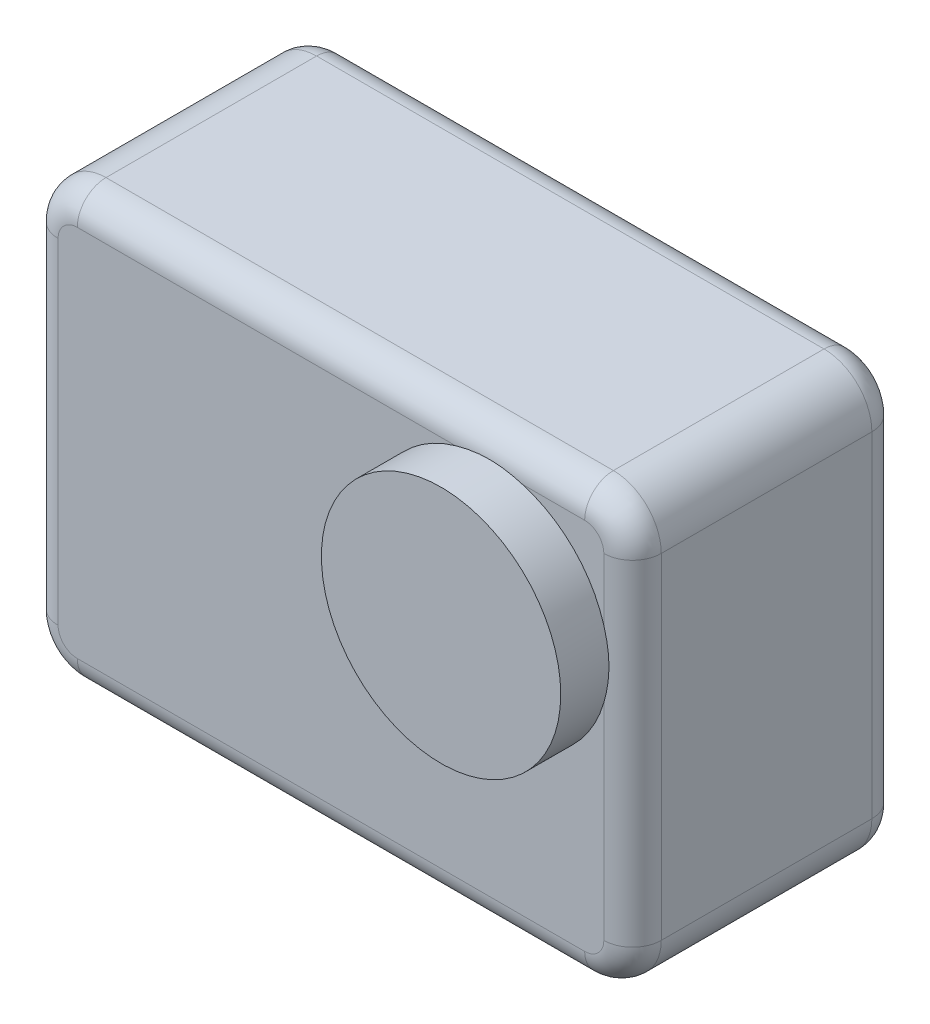
SolidWorks part; units mm, degrees
ref_plane "Front Plane" through (0, 0, 0) normal (0, 0, 1) x (1, 0, 0)
ref_plane "Top Plane" through (0, 0, 0) normal (0, 1, 0) x (1, 0, 0)
ref_plane "Right Plane" through (0, 0, 0) normal (1, 0, 0) x (0, 0, -1)
sketch "Sketch3" plane through (0, 0, 0) normal (0, 0, 1) x (1, 0, 0)
  line L1 (5, 0) -> (58, 0)
  line L2 (0, 5) -> (0, 40)
  line L3 (5, 45) -> (58, 45)
  line L4 (63, 5) -> (63, 40)
  arc A0 (5, 0) -> (0, 5) centre (5, 5) cw
  arc A1 (58, 0) -> (63, 5) centre (58, 5) ccw
  arc A2 (58, 45) -> (63, 40) centre (58, 40) cw
  arc A3 (0, 40) -> (5, 45) centre (5, 40) cw
  point P7 (0, 0)
  point P10 (63, 0)
  point P15 (0, 45)
  dimension "D3" = 5
  dimension "D1" = 45
  dimension "D2" = 63
extrude "Boss-Extrude1" add sketch "Sketch3" along normal blind 28
fillet "Fillet1" radius 3 16 edges at (31.5, 0, 0) (61.5355, 1.4645, 0) (63, 22.5, 0) (61.5355, 43.5355, 0) (31.5, 45, 0) (1.4645, 43.5355, 0) (0, 22.5, 0) (1.4645, 1.4645, 0) (0, 22.5, 28) (1.4645, 43.5355, 28) (31.5, 45, 28) (61.5355, 43.5355, 28) (63, 22.5, 28) (61.5355, 1.4645, 28) (31.5, 0, 28) (1.4645, 1.4645, 28)
sketch "Sketch4" plane through (0, 0, 28) normal (0, 0, 1) x (1, 0, 0)
  line L0 (58, 42) -> (5, 42) construction
  line L1 (60, 5) -> (60, 40) construction
  circle A0 centre (48, 30) radius 12.5
  point P2 (0, 0)
  dimension "D1" = 25
  dimension "D2" = 12
  dimension "D3" = 12
extrude "Boss-Extrude3" add sketch "Sketch4" along normal mid plane 10 contours A0
